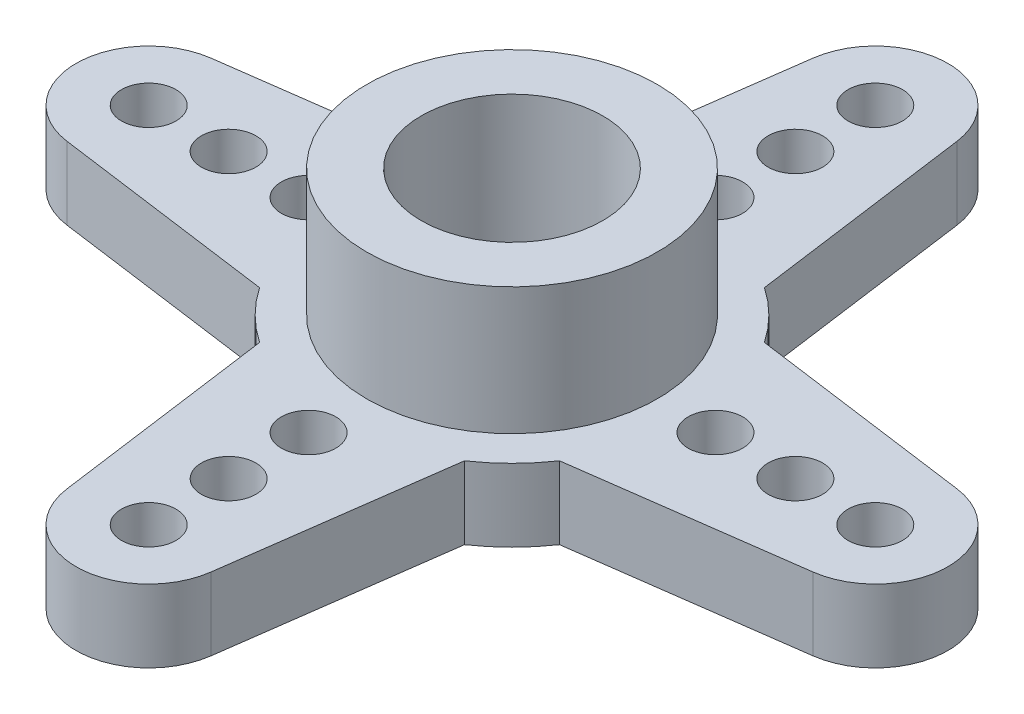
SolidWorks part; units mm, degrees
ref_plane "Plano frontal" through (0, 0, 0) normal (0, 0, 1) x (1, 0, 0)
ref_plane "Plano superior" through (0, 0, 0) normal (0, 1, 0) x (1, 0, 0)
ref_plane "Plano direito" through (0, 0, 0) normal (1, 0, 0) x (0, 0, -1)
sketch "Esboço2" plane through (0, 0, 0) normal (0, 1, 0) x (1, 0, 0)
  line L0 (0, 0) -> (-5.6, 0) construction
  line L1 (-4.1284, 2.8208) -> (-4.1284, -2.8208) construction
  line L2 (-10.2707, 1.9816) -> (-4.1284, 2.8208)
  line L3 (-10.2707, -1.9816) -> (-4.1284, -2.8208)
  line L4 (-5.6, 0) -> (-7.8, 0) construction
  line L5 (-7.8, 0) -> (-10, 0) construction
  line L6 (5.6, 0) -> (0, 0) construction
  line L7 (0, 5.6) -> (0, 0) construction
  line L8 (0, 0) -> (0, -5.6) construction
  circle A0 centre (0, 0) radius 0.75
  circle A1 centre (-5.6, 0) radius 0.75
  circle A2 centre (-7.8, 0) radius 0.75
  circle A3 centre (-10, 0) radius 0.75
  arc A4 (-4.1284, 2.8208) -> (-4.1284, -2.8208) centre (0, 0) ccw construction
  arc A5 (-4.1284, -2.8208) -> (-0.4248, -4.9819) centre (0, 0) ccw
  arc A6 (-10.2707, 1.9816) -> (-10.2707, -1.9816) centre (-10, 0) ccw
  arc A7 (4.9819, 0.4248) -> (4.9819, -0.4248) centre (5.6, 0) ccw
  arc A8 (4.9819, -0.4248) -> (4.9819, 0.4248) centre (0, 0) ccw construction
  arc A9 (4.9819, 0.4248) -> (0.4248, 4.9819) centre (0, 0) ccw
  arc A10 (4.9819, -0.4248) -> (4.9819, 0.4248) centre (5.6, 0) ccw construction
  arc A11 (-0.4248, 4.9819) -> (0.4248, 4.9819) centre (0, 5.6) ccw
  arc A12 (-0.4248, -4.9819) -> (0.4248, -4.9819) centre (0, -5.6) ccw construction
  arc A13 (0.4248, -4.9819) -> (-0.4248, -4.9819) centre (0, -5.6) ccw
  arc A14 (0.4248, -4.9819) -> (4.9819, -0.4248) centre (0, 0) ccw
  arc A15 (-0.4248, -4.9819) -> (0.4248, -4.9819) centre (0, 0) ccw construction
  arc A16 (0.4248, 4.9819) -> (-0.4248, 4.9819) centre (0, 5.6) ccw construction
  arc A17 (0.4248, 4.9819) -> (-0.4248, 4.9819) centre (0, 0) ccw construction
  arc A18 (-0.4248, 4.9819) -> (-4.1284, 2.8208) centre (0, 0) ccw
  dimension "D2" = 2
  dimension "D3" = 1.5
  dimension "D4" = 5
  dimension "D5" = 1.5
  dimension "D6" = 10
  dimension "D7" = 5.6
  dimension "D8" = 5.6415
extrude "Ressalto-extrusão1" add sketch "Esboço2" along normal blind 2
pattern_circular "PadrãoCircular1" count 4 over 360 about axis through (0, 0, 0) along (0, 1, 0) of "Ressalto-extrusão1"
sketch "Esboço3" plane through (0, 2, 0) normal (0, 1, 0) x (1, 0, 0)
  circle A0 centre (0, 0) radius 4
  circle A2 centre (0, 0) radius 2.5
  dimension "D1" = 8
  dimension "D2" = 5
extrude "Ressalto-extrusão2" add sketch "Esboço3" along normal blind 3.5
sketch "Esboço4" plane through (0, 2, 0) normal (0, 1, 0) x (1, 0, 0)
  circle A0 centre (0, 0) radius 0.75 construction
  circle A1 centre (0, 0) radius 2.5
  circle A2 centre (0, 0) radius 2.5
  circle A3 centre (0, 0) radius 0.75
  dimension "D1" = 0
extrude "Corte-extrusão1" cut sketch "Esboço4" against normal blind 1
sketch "Esboço5" plane through (0, 0, 0) normal (0, -1, 0) x (1, 0, 0)
  circle A0 centre (0, 0) radius 2.5
  circle A1 centre (0, 0) radius 3
  circle A2 centre (0, 0) radius 2.5 construction
  dimension "D1" = 0.5
extrude "Ressalto-extrusão3" add sketch "Esboço5" along normal blind 1
